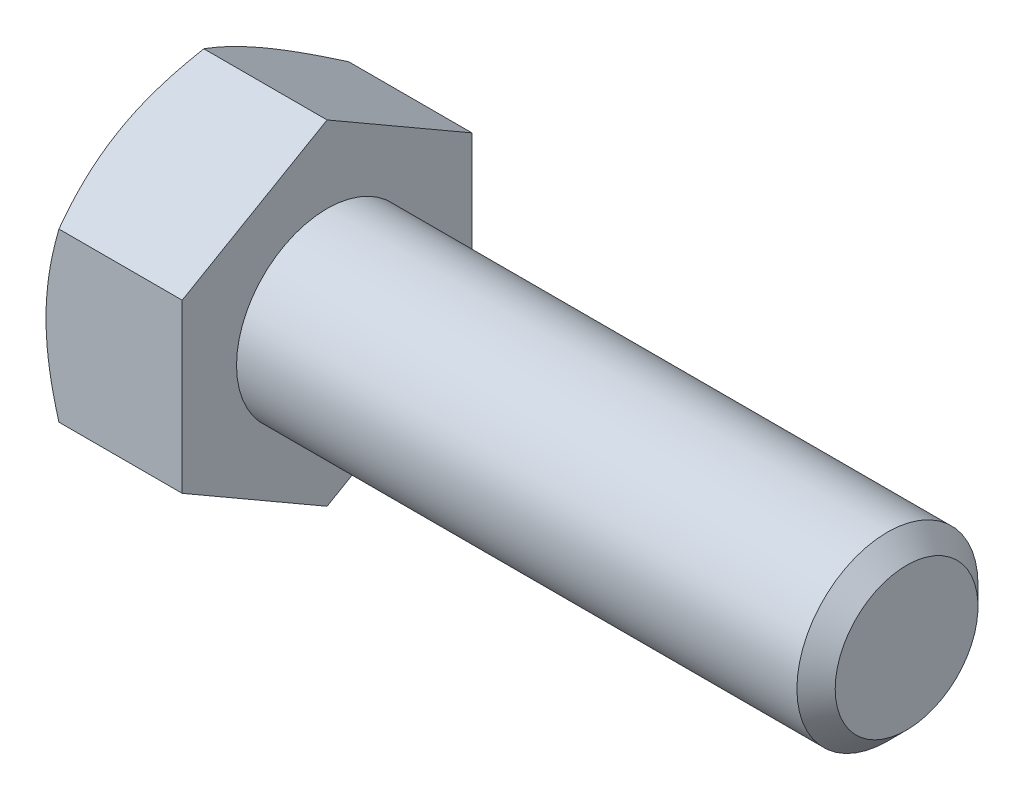
SolidWorks part; units mm, degrees
extrude "BaseHead" add sketch "Sketch1" along normal blind 5.969
sketch "Sketch1" plane through (0, 0, 0) normal (1, 0, 0) x (0, 0, -1)
  line L0 (6.35, 3.6662) -> (6.35, -3.6662)
  line L1 (-6.35, 3.6662) -> (-6.35, -3.6662)
  line L2 (6.35, -3.6662) -> (0, -7.3323)
  line L3 (0, -7.3323) -> (-6.35, -3.6662)
  line L4 (6.35, 3.6662) -> (0, 7.3323)
  line L5 (0, 7.3323) -> (-6.35, 3.6662)
  dimension "Width_flats" = 12.7
  dimension "D2" = 120
  dimension "D3" = 6.35
  dimension "D4" = 6.35
  dimension "D5" = 6.35
ref_plane "Plane1" through (0, 0, 0) normal (0, 0, 1) x (1, 0, 0)
ref_plane "Plane2" through (0, 0, 0) normal (0, 1, 0) x (1, 0, 0)
ref_plane "Plane3" through (0, 0, 0) normal (1, 0, 0) x (0, 0, -1)
sketch "BodySke" plane through (0, 0, 0) normal (0, 0, 1) x (1, 0, 0)
  line L0 (0, 3.6662) -> (0, -3.6662) construction
  line L1 (0, 0) -> (31.369, 0)
  line L2 (0, 0) -> (0, 3.9688)
  line L3 (0, 3.9688) -> (30.5295, 3.9688)
  line L4 (31.369, 0) -> (31.369, 3.1293)
  line L5 (5.969, 7.3323) -> (5.969, 3.6662) construction
  line L6 (31.369, 3.1293) -> (30.5295, 3.9688)
  line L7 (0, 0) -> (96.52, 0) construction
  line L8 (31.369, -3.1293) -> (30.5295, -3.9688) construction
  line L9 (0, -3.9688) -> (30.5295, -3.9688) construction
  line L10 (7.3787, 15.24) -> (7.3787, -2.54) construction
  line L11 (9.144, 15.24) -> (9.144, -2.54) construction
  line L12 (5.969, 3.6662) -> (5.969, -3.6662) construction
  dimension "Diameter" = 7.9375
revolve "BaseBody" add sketch "BodySke" angle 360 about L7
cosmetic thread "ThreadCosmetic" [suppressed] parameters "Thread_length"=22.225, "Thread_minor"=6.2586
sketch "Sketch3" plane through (0, 0, 0) normal (0, 0, 1) x (1, 0, 0)
  line L0 (0, 6.35) -> (4.2333, 13.6823)
  line L1 (0, 7.3323) -> (0, 3.6662) construction
  line L2 (4.2333, 13.6823) -> (4.2333, 20.0323)
  line L3 (4.2333, 20.0323) -> (-12.7, 20.0323)
  line L4 (-12.7, 20.0323) -> (-12.7, 6.35)
  line L5 (-12.7, 6.35) -> (0, 6.35)
  line L6 (0, 0) -> (99.06, 0) construction
  line L7 (5.969, 7.3323) -> (0, 7.3323) construction
  dimension "D4" = 6.35
  dimension "D1" = 6.35
  dimension "D2" = 6.35
  dimension "D3" = 12.7
  dimension "Head_ch_ang" = 30
revolve "HeadChamfer" cut sketch "Sketch3" angle 360 about L6
fillet "HeadFillet" [suppressed] radius 0.762
sketch "ThdSchSke" plane through (0, 0, 0) normal (0, 0, 1) x (1, 0, 0)
  line L0 (9.144, -3.1293) -> (8.5562, -3.9688)
  line L1 (9.144, -3.1293) -> (9.7318, -3.9688)
  line L2 (9.7318, -3.9688) -> (9.7318, -4.9609)
  line L3 (-3.175, 0) -> (5.1513, 0) construction
  line L5 (9.7318, -4.9609) -> (8.5562, -4.9609)
  line L6 (8.5562, -4.9609) -> (8.5562, -3.9688)
  dimension "Thread_minor" = 6.2586
  dimension "Diameter" = 7.9375
  dimension "Start" = 9.144
revolve "ThreadSchematic" [suppressed] cut sketch "ThdSchSke" angle 360 about L3
pattern_linear "ThdSchPat" [suppressed]
equation "\"D3@Sketch1\" = \"Width_flats@Sketch1\" / 2"
equation "\"D4@Sketch1\" = \"D3@Sketch1\""
equation "\"D5@Sketch1\" = \"D4@Sketch1\""
equation "\"Thread_minor@ThreadCosmetic\" = \"Minor_dia@BodySke\""
equation "\"D1@Sketch3\" = \"Width_flats@Sketch1\" / 2"
equation "\"Thread_length@ThreadCosmetic\" = ((sgn( (\"Length@BodySke\" - \"Advance@BodySke\" ) - \"Thread_nom@BodySke\" )-1)*( (\"Length@BodySke\" - \"Advance@BodySke\" ) - \"Thread_nom@BodySke\" ))/-2+ \"Thread_nom@BodySke\""
equation "\"Thread_minor@ThdSchSke\" = \"Minor_dia@BodySke\""
equation "\"Diameter@ThdSchSke\" = \"Diameter@BodySke\""
equation "\"Overcut@ThdSchSke\" = \"Diameter@BodySke\" * 1.25"
equation "\"Start@ThdSchSke\" = \"Head_ht@BaseHead\" + \"Length@BodySke\" - \"Thread_length@ThreadCosmetic\"  '---Non-countersunk---"
equation "\"Num_threads@ThdSchPat\" = int( \"Thread_length@ThreadCosmetic\" / \"Advance@BodySke\" + 0.999 )  + 1"
equation "\"Advance@ThdSchPat\" = \"Thread_length@ThreadCosmetic\" /  (\"Num_threads@ThdSchPat\" - 1) 'relax it"
equation "\"Num_threads@ThdSchPat\" = \"Num_threads@ThdSchPat\" - sgn( \"Num_threads@ThdSchPat\" - 1) '---chamfered tips only---"
